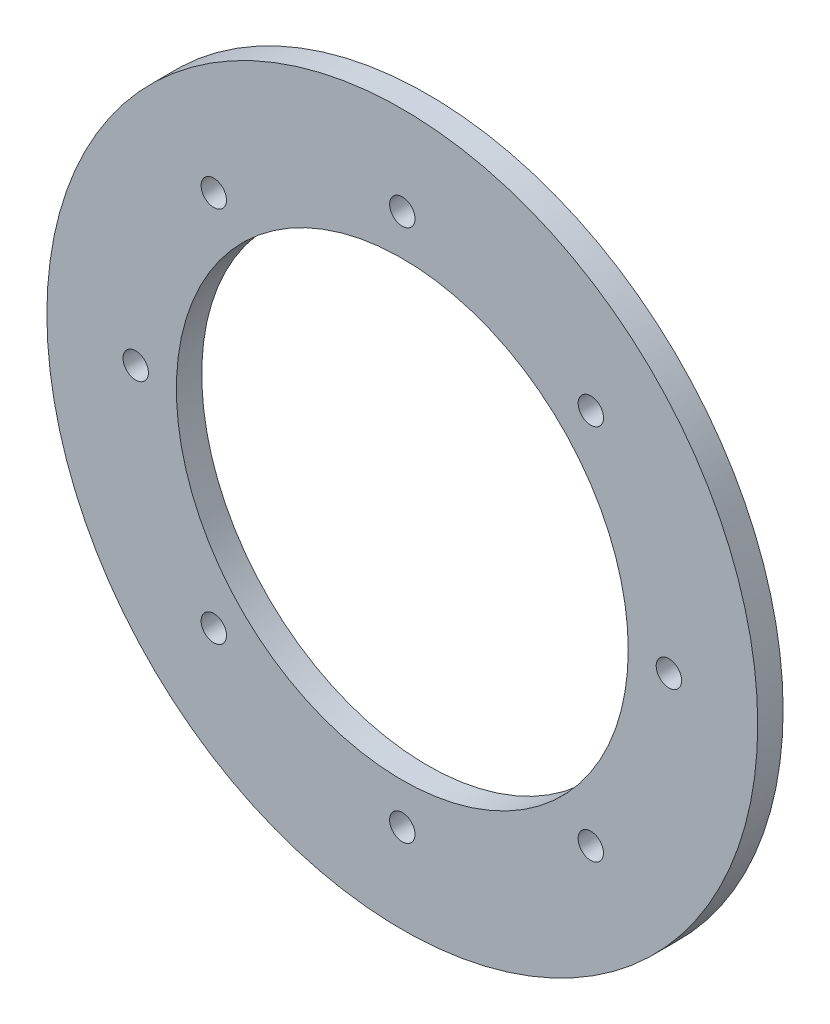
SolidWorks part; units mm, degrees
material "Thornel Mat VMA"
ref_plane "Front Plane" through (0, 0, 0) normal (0, 0, 1) x (1, 0, 0)
ref_plane "Top Plane" through (0, 0, 0) normal (0, 1, 0) x (1, 0, 0)
ref_plane "Right Plane" through (0, 0, 0) normal (1, 0, 0) x (0, 0, -1)
sketch "Sketch1" plane through (0, 0, 0) normal (0, 0, 1) x (1, 0, 0)
  circle A0 centre (0, 0) radius 44.5 construction
  circle A1 centre (0, 0) radius 44.5
  circle A2 centre (37.1231, -37.1231) radius 2.5 construction
  circle A3 centre (52.5, 0) radius 2.5 construction
  circle A4 centre (0, -52.5) radius 2.5 construction
  circle A5 centre (-37.1231, -37.1231) radius 2.5 construction
  circle A6 centre (-52.5, 0) radius 2.5 construction
  circle A7 centre (37.1231, 37.1231) radius 2.5 construction
  circle A8 centre (-37.1231, 37.1231) radius 2.5 construction
  circle A9 centre (0, 52.5) radius 2.5 construction
  circle A10 centre (37.1231, -37.1231) radius 2.5
  circle A11 centre (52.5, 0) radius 2.5
  circle A12 centre (0, -52.5) radius 2.5
  circle A13 centre (-37.1231, -37.1231) radius 2.5
  circle A14 centre (-52.5, 0) radius 2.5
  circle A15 centre (37.1231, 37.1231) radius 2.5
  circle A16 centre (-37.1231, 37.1231) radius 2.5
  circle A17 centre (0, 52.5) radius 2.5
  circle A18 centre (0, 0) radius 70
  dimension "D1" = 140
extrude "Boss-Extrude1" add sketch "Sketch1" along normal blind 5
